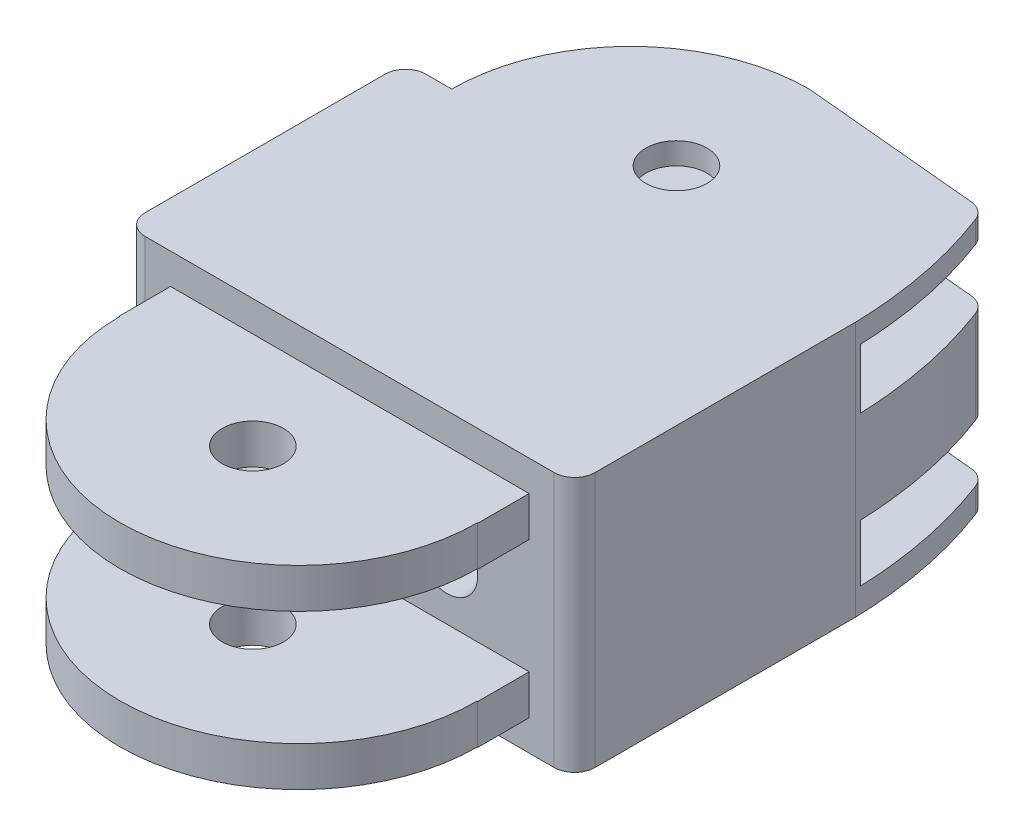
SolidWorks part; units mm, degrees
ref_plane "Front Plane" through (0, 0, 0) normal (0, 0, 1) x (1, 0, 0)
ref_plane "Top Plane" through (0, 0, 0) normal (0, 1, 0) x (1, 0, 0)
ref_plane "Right Plane" through (0, 0, 0) normal (1, 0, 0) x (0, 0, -1)
sketch "Sketch2" plane through (0, 0, 0) normal (0, 0, 1) x (1, 0, 0)
  line L0 (-24.2561, -24.0702) -> (-22.0061, -24.0702) construction
  line L1 (-24.2561, -17.8202) -> (-2.2017, -17.8202) construction
  line L2 (-24.2561, -17.8202) -> (-24.2561, -30.3202) construction
  line L3 (-24.2561, -30.3202) -> (-2.2017, -30.3202) construction
  line L4 (-2.2017, -17.8202) -> (-2.2017, -30.3202) construction
  line L5 (-2.2017, -24.0702) -> (-4.4517, -24.0702) construction
  line L6 (-22.0061, -24.0702) -> (-22.0061, -30.3202) construction
  line L7 (-4.4517, -24.0702) -> (-4.4517, -30.3202) construction
  line L8 (-24.2561, -17.8202) -> (-24.2561, -19.3148) construction
  line L9 (-24.2561, -19.3148) -> (-22.0061, -19.3148) construction
  line L10 (-2.2017, -17.8202) -> (-2.2017, -19.3148) construction
  line L11 (-2.2017, -19.3148) -> (-4.4517, -19.3148) construction
  line L12 (-2.2017, -30.3202) -> (-2.2017, -28.8202) construction
  line L13 (-2.2017, -28.8202) -> (-4.4517, -28.8202) construction
  line L14 (-24.2561, -30.3202) -> (-24.2561, -28.8202) construction
  line L15 (-24.2561, -28.8202) -> (-22.0061, -28.8202) construction
  line L17 (-22.0061, -28.8202) -> (-4.4517, -28.8202)
  line L18 (-22.0061, -28.8202) -> (-22.0061, -26.8702)
  line L19 (-22.0061, -26.8702) -> (-4.4517, -26.8702)
  line L20 (-4.4517, -28.8202) -> (-4.4517, -26.8702)
  line L21 (-22.0061, -28.8202) -> (-4.4517, -26.8702) construction
  line L22 (-22.0061, -26.8702) -> (-4.4517, -28.8202) construction
  line L23 (-22.0061, -19.3148) -> (-4.4517, -19.3148)
  line L24 (-22.0061, -19.3148) -> (-22.0061, -21.2648)
  line L25 (-22.0061, -21.2648) -> (-4.4517, -21.2648)
  line L26 (-4.4517, -19.3148) -> (-4.4517, -21.2648)
  line L27 (-22.0061, -19.3148) -> (-4.4517, -21.2648) construction
  line L28 (-22.0061, -21.2648) -> (-4.4517, -19.3148) construction
  point P19 (-13.2289, -27.8452)
  point P22 (-13.2289, -20.2898)
extrude "Boss-Extrude1" add sketch "Sketch2" along normal blind 8.75
sketch "Sketch3" plane through (0, -19.3148, 0) normal (0, 1, 0) x (1, 0, 0)
  line L0 (-4.4517, 0) -> (-22.0061, 0) construction
  line L1 (-4.4517, -8.75) -> (-22.0061, -8.75) construction
  arc A0 (-13.2289, -8.75) -> (-4.4789, 0) centre (-13.2289, 0) ccw
  arc A1 (-13.2289, -8.75) -> (-21.9789, 0) centre (-13.2289, 0) cw
  spline S0 degree 2 poles (-22.0061, -8.75) (-13.2289, -12.4735) (-4.4517, -8.75) knots 0 0 0 1 1 1
  spline S1 degree 2 poles (-21.9789, 0) (-25.927, -4.2429) (-22.0061, -8.75) knots 0 0 0 1 1 1
  spline S2 degree 2 poles (-4.4789, 0) (1.1383, -4.1517) (-4.4517, -8.75) knots 0 0 0 1 1 1
extrude "Cut-Extrude1" cut sketch "Sketch3" against normal through all contours S0 S2 A0 A1 S1
sketch "Sketch4" plane through (0, 0, 0) normal (0, 0, -1) x (-1, 0, 0)
  line L0 (22.0061, -19.3148) -> (24.2561, -19.3148) construction
  line L1 (22.0061, -19.3148) -> (4.4789, -19.3148) construction
  line L2 (22.0061, -19.3148) -> (22.0061, -28.8202) construction
  line L3 (22.0061, -28.8202) -> (4.4789, -28.8202) construction
  line L4 (4.4789, -19.3148) -> (4.4789, -28.8202) construction
  line L5 (22.0061, -19.3148) -> (4.4789, -28.8202) construction
  line L6 (22.0061, -28.8202) -> (4.4789, -19.3148) construction
  line L7 (24.2561, -19.3148) -> (24.2561, -17.8148) construction
  line L8 (4.4789, -28.8202) -> (2.2289, -28.8202) construction
  line L9 (2.2289, -28.8202) -> (2.2289, -30.3202) construction
  line L11 (24.2561, -17.8148) -> (2.2289, -17.8148)
  line L12 (24.2561, -17.8148) -> (24.2561, -30.3202)
  line L13 (24.2561, -30.3202) -> (2.2289, -30.3202)
  line L14 (2.2289, -17.8148) -> (2.2289, -30.3202)
  line L15 (24.2561, -17.8148) -> (2.2289, -30.3202) construction
  line L16 (24.2561, -30.3202) -> (2.2289, -17.8148) construction
  point P4 (13.2425, -24.0675)
  point P14 (13.2425, -24.0675)
extrude "Boss-Extrude2" add sketch "Sketch4" along normal blind 25 contours L12 L13 L14 L11
sketch "Sketch5" plane through (0, -19.3148, 0) normal (0, 1, 0) x (1, 0, 0)
  line L0 (-13.2289, -8.75) -> (-13.2289, -2.25) construction
  arc A0 (-21.9789, 0) -> (-4.4789, 0) centre (-13.2289, 0) ccw construction
  circle A1 centre (-13.2289, -2.25) radius 1.5
extrude "Cut-Extrude2" cut sketch "Sketch5" against normal blind 12 contours A1
sketch "Sketch6" plane through (0, 0, 0) normal (0, 0, 1) x (1, 0, 0)
  line L0 (-24.2561, -30.3202) -> (-2.2289, -30.3202)
  line L1 (-2.2289, -30.3202) -> (-2.2289, -17.8148)
  line L2 (-2.2289, -17.8148) -> (-24.2561, -17.8148)
  line L3 (-24.2561, -17.8148) -> (-24.2561, -30.3202)
  line L4 (-22.0061, -28.8202) -> (-4.4517, -28.8202)
  line L5 (-4.4517, -28.8202) -> (-4.4517, -26.8702)
  line L6 (-4.4517, -28.8202) -> (-4.4517, -26.8702) construction
  line L7 (-4.4517, -26.8702) -> (-22.0061, -26.8702)
  line L8 (-22.0061, -28.8202) -> (-22.0061, -26.8702)
  line L9 (-22.0061, -21.2648) -> (-22.0061, -19.3148)
  line L10 (-22.0061, -19.3148) -> (-4.4517, -19.3148)
  line L11 (-4.4517, -19.3148) -> (-4.4517, -21.2648)
  line L12 (-4.4517, -21.2648) -> (-22.0061, -21.2648)
extrude "Cut-Extrude3" cut sketch "Sketch6" against normal blind 2.5
sketch "Sketch7" plane through (0, -17.8148, 0) normal (0, 1, 0) x (1, 0, 0)
  line L0 (-2.2289, 25) -> (-2.2289, 2.5) construction
  line L1 (-24.2561, 25) -> (-2.2289, 25) construction
  line L3 (-21.9925, 16.25) -> (-24.2561, 16.25)
  line L7 (-13.2425, 25) -> (-3.8818, 24.1286)
  circle A0 centre (-13.2425, 18.5) radius 1.5
  arc A1 (-13.2425, 25) -> (-21.9925, 16.25) centre (-13.2425, 16.25) ccw
  spline S0 degree 3 poles (-24.2561, 16.25) (-34.3688, 22.1782) (-14.7123, 52.0329) (16.6293, 22.4638) (-2.2289, 16.25) knots 0 0 0 0 0.431251 1 1 1 1
  spline S1 degree 2 poles (-3.8818, 24.1286) (-2.3288, 20.3726) (-2.2289, 16.25) knots 0 0 0 1 1 1
extrude "Cut-Extrude4" cut sketch "Sketch7" against normal blind 13
sketch "Sketch8" plane through (0, 0, -2.5) normal (0, 0, 1) x (1, 0, 0)
  line L0 (-24.2561, -24.0675) -> (-18.0111, -24.0675) construction
  line L1 (-24.2561, -17.8148) -> (-24.2561, -30.3202) construction
  line L2 (-2.2289, -24.0675) -> (-8.474, -24.0675) construction
  line L3 (-2.2289, -30.3202) -> (-2.2289, -17.8148) construction
  line L4 (-4.4517, -21.2648) -> (-4.4517, -24.0675) construction
  line L5 (-4.4517, -24.0675) -> (-8.474, -24.0675) construction
  circle A0 centre (-18.0111, -24.0675) radius 1.5
  circle A1 centre (-8.474, -24.0675) radius 1.5
extrude "Cut-Extrude5" cut sketch "Sketch8" against normal blind 28
fillet "Fillet3" radius 1 4 edges at (-24.2561, -24.0675, -2.5) (-24.2561, -24.0675, -16.25) (-2.2289, -24.0675, -2.5) (-3.8818, -24.0675, -24.1286)
ref_plane "Plane4" through (0, 0, -32.5) normal (0, 0, 1) x (1, 0, 0)
sketch "Sketch9" plane through (0, 0, -32.5) normal (0, 0, 1) x (1, 0, 0)
  line L0 (-24.3405, -17.7669) -> (-24.3405, -18.8808) construction
  line L1 (-24.3405, -17.7669) -> (-2.1446, -17.7669) construction
  line L2 (-24.3405, -17.7669) -> (-24.3405, -30.368) construction
  line L3 (-24.3405, -30.368) -> (-2.1446, -30.368) construction
  line L4 (-2.1446, -17.7669) -> (-2.1446, -30.368) construction
  line L5 (-24.3405, -17.7669) -> (-2.1446, -30.368) construction
  line L6 (-24.3405, -30.368) -> (-2.1446, -17.7669) construction
  line L7 (-24.3405, -30.368) -> (-24.3405, -29.1278) construction
  line L8 (-24.3405, -18.8808) -> (-2.1446, -18.8808)
  line L9 (-24.3405, -18.8808) -> (-24.3405, -21.7989)
  line L10 (-24.3405, -21.7989) -> (-2.1446, -21.7989)
  line L11 (-2.1446, -18.8808) -> (-2.1446, -21.7989)
  line L12 (-24.3405, -18.8808) -> (-2.1446, -21.7989) construction
  line L13 (-24.3405, -21.7989) -> (-2.1446, -18.8808) construction
  line L14 (-13.2425, -26.3361) -> (-13.2425, -24.0675) construction
  line L15 (-24.3405, -29.1278) -> (-2.1446, -29.1278)
  line L16 (-24.3405, -29.1278) -> (-24.3405, -26.3361)
  line L17 (-24.3405, -26.3361) -> (-2.1446, -26.3361)
  line L18 (-2.1446, -29.1278) -> (-2.1446, -26.3361)
  line L19 (-24.3405, -29.1278) -> (-2.1446, -26.3361) construction
  line L20 (-24.3405, -26.3361) -> (-2.1446, -29.1278) construction
  line L21 (-13.2425, -24.0675) -> (-13.2425, -21.7989) construction
  point P4 (-13.2425, -24.0675)
  point P8 (-13.2425, -20.3398)
  point P13 (-13.2425, -27.7319)
  point P16 (0, 0)
  point P18 (-24.2884, -18.8808)
  point P19 (0, 0)
  point P20 (-24.3405, -29.1278)
extrude "Cut-Extrude6" cut sketch "Sketch9" along normal blind 16
sketch "Sketch10" plane through (0, 0, -16.5) normal (0, 0, -1) x (-1, 0, 0)
  line L0 (2.2363, -26.3361) -> (21.989, -26.3361) construction
  line L1 (21.989, -29.1278) -> (3.8638, -29.1278)
  line L2 (21.989, -29.1278) -> (21.989, -26.3361)
  line L3 (21.989, -26.3361) -> (3.8638, -26.3361)
  line L4 (3.8638, -29.1278) -> (3.8638, -26.3361)
  line L5 (21.989, -29.1278) -> (3.8638, -26.3361) construction
  line L6 (21.989, -26.3361) -> (3.8638, -29.1278) construction
  line L7 (2.2363, -18.8808) -> (21.989, -18.8808) construction
  line L8 (21.989, -21.7989) -> (3.8638, -21.7989)
  line L9 (21.989, -21.7989) -> (21.989, -18.8808)
  line L10 (21.989, -18.8808) -> (3.8638, -18.8808)
  line L11 (3.8638, -21.7989) -> (3.8638, -18.8808)
  line L12 (21.989, -21.7989) -> (3.8638, -18.8808) construction
  line L13 (21.989, -18.8808) -> (3.8638, -21.7989) construction
  point P4 (12.9264, -27.7319)
  point P12 (12.9264, -20.3398)
extrude "Cut-Extrude7" cut sketch "Sketch10" against normal blind 5
